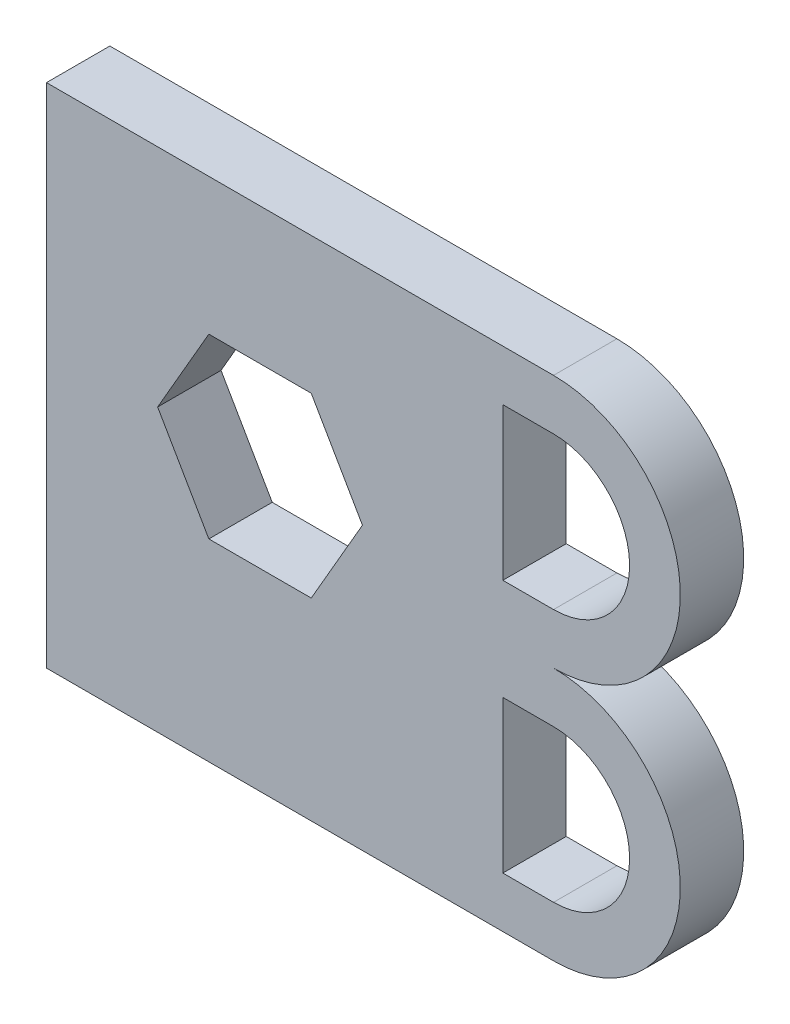
SolidWorks part; units mm, degrees
ref_plane "Plan de face" through (0, 0, 0) normal (0, 0, 1) x (1, 0, 0)
ref_plane "Plan de dessus" through (0, 0, 0) normal (0, 1, 0) x (1, 0, 0)
ref_plane "Plan de droite" through (0, 0, 0) normal (1, 0, 0) x (0, 0, -1)
sketch "Esquisse1" plane through (0, 0, 0) normal (0, 0, 1) x (1, 0, 0)
  line L0 (0, 0) -> (80, 0)
  line L1 (0, 0) -> (0, 80)
  line L2 (-16.5154, 40) -> (92.4158, 40) construction
  line L3 (0, 80) -> (80, 80)
  line L7 (72, 8) -> (72, 32)
  line L8 (72, 32) -> (80, 32)
  line L9 (80, 8) -> (72, 8)
  line L10 (72, 48) -> (80, 48)
  line L11 (72, 72) -> (72, 48)
  line L12 (80, 72) -> (72, 72)
  arc A0 (80, 0) -> (80, 40) centre (80, 20) ccw
  arc A1 (80, 80) -> (80, 40) centre (80, 60) cw
  arc A3 (80, 32) -> (80, 8) centre (80, 20) cw
  arc A4 (80, 48) -> (80, 72) centre (80, 60) ccw
  point P11 (0, 40)
  dimension "D1" = 20
  dimension "D3" = 12
  dimension "D2" = 80
  dimension "D4" = 8
extrude "Boss.-Extru.1" add sketch "Esquisse1" along normal blind 10
sketch "Esquisse2" plane through (0, 0, 10) normal (0, 0, 1) x (1, 0, 0)
  line L1 (49.8504, 44.4502) -> (41.7727, 58.4412)
  line L2 (41.7727, 58.4412) -> (25.6173, 58.4412)
  line L3 (25.6173, 58.4412) -> (17.5396, 44.4502)
  line L4 (17.5396, 44.4502) -> (25.6173, 30.4592)
  line L5 (25.6173, 30.4592) -> (41.7727, 30.4592)
  line L6 (41.7727, 30.4592) -> (49.8504, 44.4502)
  circle A0 centre (33.695, 44.4502) radius 13.991 construction
extrude "Enlèv. mat.-Extru.3" cut sketch "Esquisse2" against normal through all
